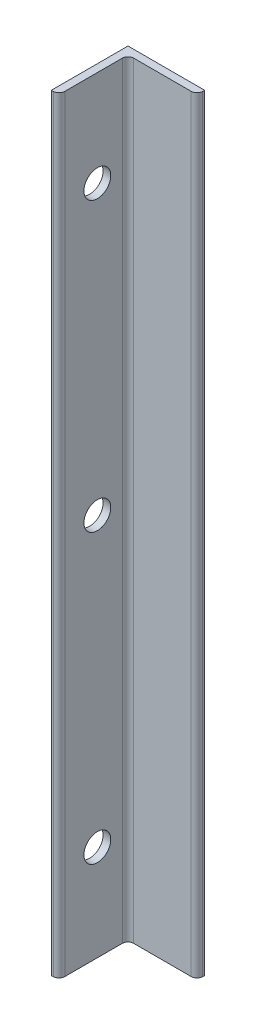
SolidWorks part; units mm, degrees
material "ASTM A36 Steel"
ref_plane "Front Plane" through (0, 0, 0) normal (0, 0, 1) x (1, 0, 0)
ref_plane "Top Plane" through (0, 0, 0) normal (0, 1, 0) x (1, 0, 0)
ref_plane "Right Plane" through (0, 0, 0) normal (1, 0, 0) x (0, 0, -1)
sketch "Sketch1" plane through (0, 0, 0) normal (0, 1, 0) x (1, 0, 0)
  line L0 (-27.4999, 29.2132) -> (-67.4999, 29.2132)
  line L1 (-67.4999, 29.2132) -> (-67.4999, -10.7868)
  line L2 (-67.4999, -10.7868) -> (-66.4999, -10.7868)
  line L3 (-63.4999, -7.7868) -> (-63.4999, 22.2132)
  line L4 (-60.4999, 25.2132) -> (-30.4999, 25.2132)
  line L5 (-27.4999, 28.2132) -> (-27.4999, 29.2132)
  arc A0 (-66.4999, -10.7868) -> (-63.4999, -7.7868) centre (-66.4999, -7.7868) ccw
  arc A1 (-63.4999, 22.2132) -> (-60.4999, 25.2132) centre (-60.4999, 22.2132) cw
  arc A2 (-30.4999, 25.2132) -> (-27.4999, 28.2132) centre (-30.4999, 28.2132) ccw
  point P8 (-63.4999, -10.7868)
  point P13 (-27.4999, 25.2132)
  dimension "D5" = 3
  dimension "D1" = 40
  dimension "D2" = 40
  dimension "D3" = 4
  dimension "D4" = 4
extrude "Boss-Extrude1" add sketch "Sketch1" along normal blind 400
sketch "Sketch2" plane through (-63.4999, 0, 0) normal (1, 0, 0) x (0, 0, -1)
  line L0 (-7.7868, 400) -> (-7.7868, 0) construction
  line L1 (-10.7868, 400) -> (-10.7868, 0) construction
  circle A0 centre (9.2132, 200) radius 7
  circle A1 centre (9.2132, 50) radius 7
  circle A2 centre (9.2132, 350) radius 7
  point P8 (-7.7868, 200)
  dimension "D1" = 14
  dimension "D2" = 14
  dimension "D3" = 14
  dimension "D4" = 0
  dimension "D5" = 150
  dimension "D6" = 150
  dimension "D7" = 20
  dimension "D8" = 20
extrude "Cut-Extrude1" cut sketch "Sketch2" against normal blind 10
